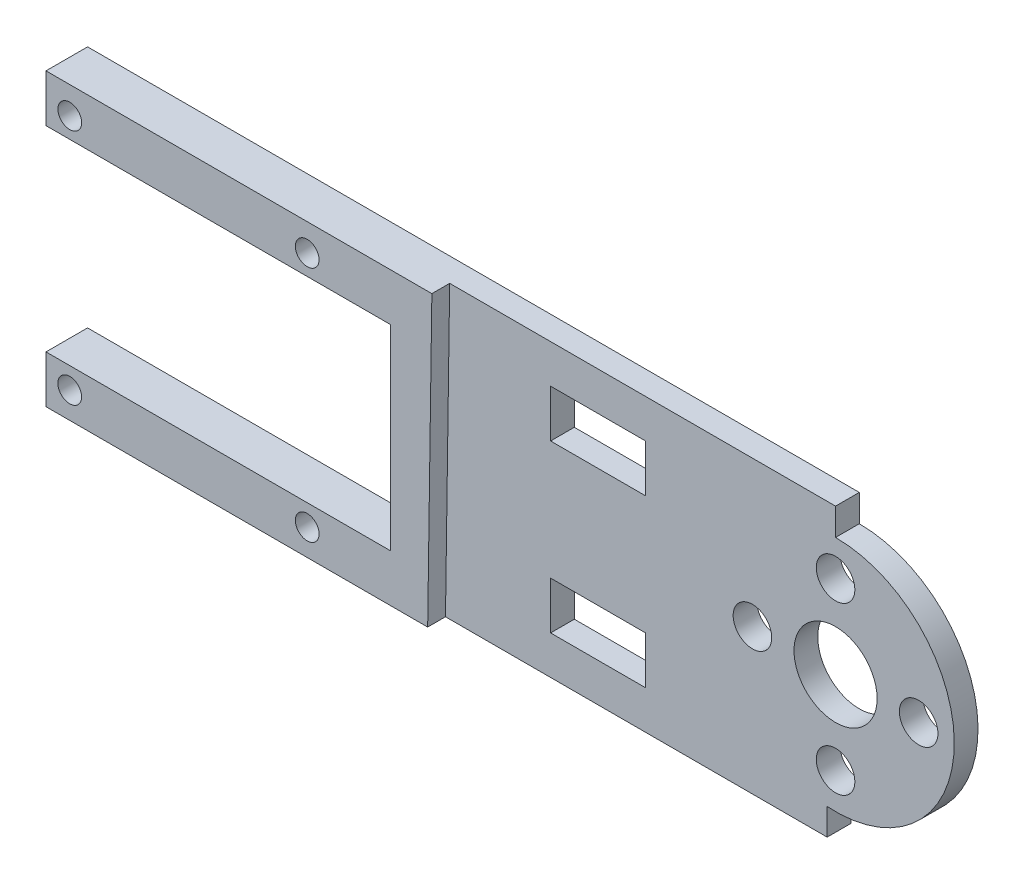
SolidWorks part; units mm, degrees
ref_plane "Front Plane" through (0, 0, 0) normal (0, 0, 1) x (1, 0, 0)
ref_plane "Top Plane" through (0, 0, 0) normal (0, 1, 0) x (1, 0, 0)
ref_plane "Right Plane" through (0, 0, 0) normal (1, 0, 0) x (0, 0, -1)
sketch "Sketch1" plane through (0, 0, 0) normal (0, 0, 1) x (1, 0, 0)
  line L1 (-4.8336, 12.25) -> (5.1664, 12.25)
  line L3 (-4.8336, -12.25) -> (5.1664, -12.25)
  line L5 (-4.8336, 12.25) -> (-24.8336, 12.25)
  line L6 (-24.8336, 12.25) -> (-24.8336, 8.25)
  line L12 (5.1664, 12.25) -> (40.1664, 12.25)
  line L13 (40.1664, 12.25) -> (40.1664, 9.9642)
  line L14 (39.4596, -12.25) -> (5.1664, -12.25)
  line L15 (-24.8336, 8.25) -> (4.1664, 8.25)
  line L16 (39.4596, -10.0108) -> (39.4596, -12.25)
  line L17 (16.1665, 9) -> (24.1665, 9)
  line L18 (16.1665, 9) -> (16.1665, 5)
  line L19 (16.1665, 5) -> (24.1665, 5)
  line L20 (24.1665, 9) -> (24.1665, 5)
  line L21 (16.1665, 9) -> (24.1665, 5) construction
  line L22 (16.1665, 5) -> (24.1665, 9) construction
  line L23 (16.1665, -5) -> (24.1665, -5)
  line L24 (16.1665, -5) -> (16.1665, -9)
  line L25 (16.1665, -9) -> (24.1665, -9)
  line L26 (24.1665, -5) -> (24.1665, -9)
  line L27 (16.1665, -5) -> (24.1665, -9) construction
  line L28 (16.1665, -9) -> (24.1665, -5) construction
  line L29 (4.1664, 8.25) -> (4.1664, -8.25)
  line L30 (4.1664, -8.25) -> (-24.8336, -8.25)
  line L31 (-24.8336, -8.25) -> (-24.8336, -12.25)
  line L32 (-24.8336, -12.25) -> (-4.8336, -12.25)
  arc A2 (39.4596, -10.0108) -> (40.1664, 9.9642) centre (40.1664, -0.0358) ccw
  circle A3 centre (40.1664, 6.9642) radius 1.625
  circle A4 centre (47.1664, -0.0358) radius 1.625
  circle A5 centre (40.1664, -7.0358) radius 1.625
  circle A6 centre (33.1664, -0.0358) radius 1.625
  circle A7 centre (40.1664, -0.0358) radius 3.5
  circle A8 centre (-2.8336, 9.9642) radius 1.125
  circle A9 centre (-2.8336, -10.0358) radius 1.125
  circle A10 centre (-22.8336, 9.9642) radius 1.125
  circle A11 centre (-22.8336, -10.0358) radius 1.125
  point P4 (0, 0)
  point P15 (0, 0)
  point P22 (20.1665, 7)
  point P35 (20.1665, -7)
  point P45 (0, 0)
  dimension "D3" = 2.25
  dimension "D4" = 2.25
  dimension "D11" = 20
  dimension "D12" = 3.25
  dimension "D15" = 7
  dimension "D8" = 2.25
  dimension "D16" = 2.25
  dimension "D5" = 43
  dimension "D6" = 24.5
  dimension "D7" = 24.5
  dimension "D9" = 12.25
  dimension "D10" = 35
  dimension "D13" = 7
  dimension "D17" = 20
  dimension "D18" = 7
  dimension "D19" = 20
  dimension "D20" = 4
  dimension "D21" = 4
  dimension "D22" = 8
  dimension "D23" = 8
  dimension "D24" = 10
  dimension "D25" = 10
  dimension "D26" = 20
  dimension "D27" = 20
  dimension "D28" = 4
  dimension "D29" = 4
  dimension "D14" = 4
extrude "Boss-Extrude1" add sketch "Sketch1" along normal blind 2
sketch "Sketch2" plane through (0, 0, 2) normal (0, 0, 1) x (1, 0, 0)
  line L0 (-24.8336, 12.25) -> (7.6664, 12.25)
  line L1 (40.1664, 12.25) -> (-24.8336, 12.25) construction
  line L2 (7.6664, 12.25) -> (7.313, -12.25)
  line L3 (-24.8336, -12.25) -> (39.4596, -12.25) construction
  line L4 (7.313, -12.25) -> (-24.8336, -12.25)
  line L5 (-24.8336, -12.25) -> (-24.8336, -8.25)
  line L6 (-24.8336, -8.25) -> (4.1664, -8.25)
  line L7 (4.1664, -8.25) -> (4.1664, 8.25)
  line L8 (4.1664, 8.25) -> (-24.8336, 8.25)
  line L9 (-24.8336, 8.25) -> (-24.8336, 12.25)
extrude "Boss-Extrude2" add sketch "Sketch2" along normal blind 1.5
sketch "Sketch4" plane through (0, 0, 0) normal (0, 0, -1) x (-1, 0, 0)
  circle A0 centre (2.8336, 9.9642) radius 1
  circle A1 centre (2.8336, -10.0358) radius 1
  circle A2 centre (22.8336, -10.0358) radius 1
  circle A3 centre (22.8336, 9.9642) radius 1
extrude "Cut-Extrude1" cut sketch "Sketch4" against normal through all
